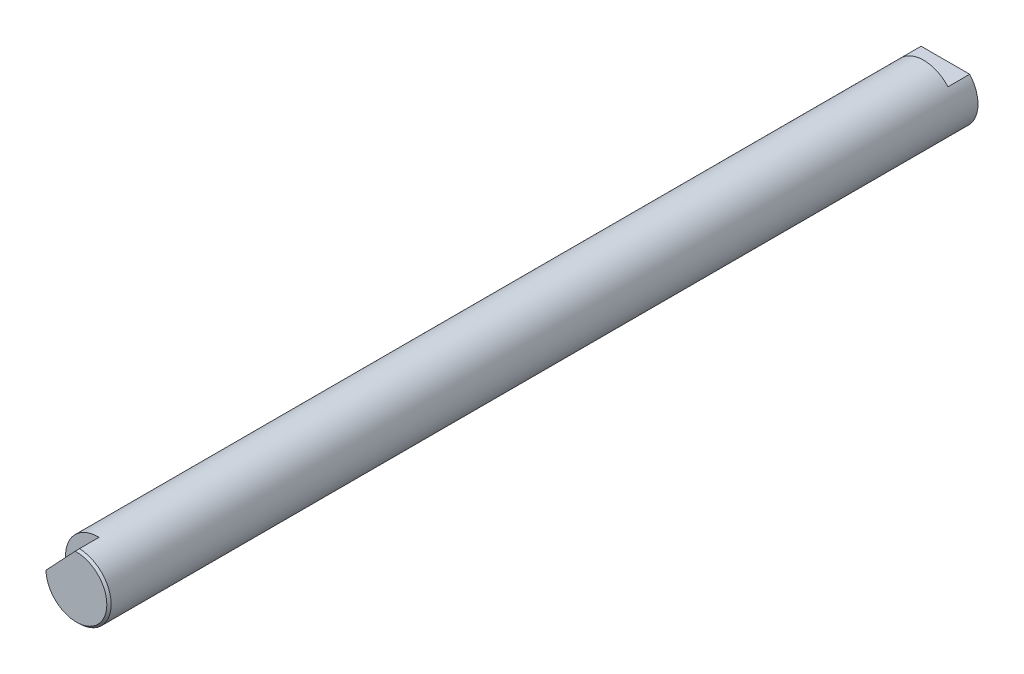
SolidWorks part; units mm, degrees
material "PW80:Mi:0:6:C1:0:1:2:Re:26:"
ref_plane "Plan1" through (0, 0, 0) normal (0, 0, 1) x (1, 0, 0)
ref_plane "Plan2" through (0, 0, 0) normal (0, 1, 0) x (1, 0, 0)
ref_plane "Plan3" through (0, 0, 0) normal (1, 0, 0) x (0, 0, -1)
sketch "Esquisse1" plane through (0, 0, 0) normal (0, 0, 1) x (1, 0, 0)
  circle A0 centre (0, 0) radius 15
extrude "Base-Extrusion" add sketch "Esquisse1" along normal blind 400
chamfer "Chanfrein1" distance 1 angle 45
sketch "Esquisse2" plane through (0, 0, 400) normal (0, 0, 1) x (1, 0, 0)
  line L0 (17.0873, 32.7418) -> (-26.8013, -13.8821)
  line L1 (-6.0795, 37.31) -> (-153.4458, -119.2408) construction
  line L2 (17.0873, 32.7418) -> (5.782, 43.3838)
  line L3 (5.782, 43.3838) -> (-38.6744, -3.8434)
  line L4 (-38.6744, -3.8434) -> (-26.8013, -13.8821)
  dimension "D1" = 20
extrude "Enlèv. mat.-Extru.1" cut sketch "Esquisse2" against normal blind 10
sketch "Esquisse3" plane through (0, 0, 0) normal (0, 0, -1) x (-1, 0, 0)
  line L1 (-20, 20) -> (30, 20)
  line L2 (-20, 20) -> (-20, 10)
  line L3 (-20, 10) -> (30, 10)
  line L4 (30, 20) -> (30, 10)
extrude "Enlèv. mat.-Extru.2" cut sketch "Esquisse3" against normal blind 10
